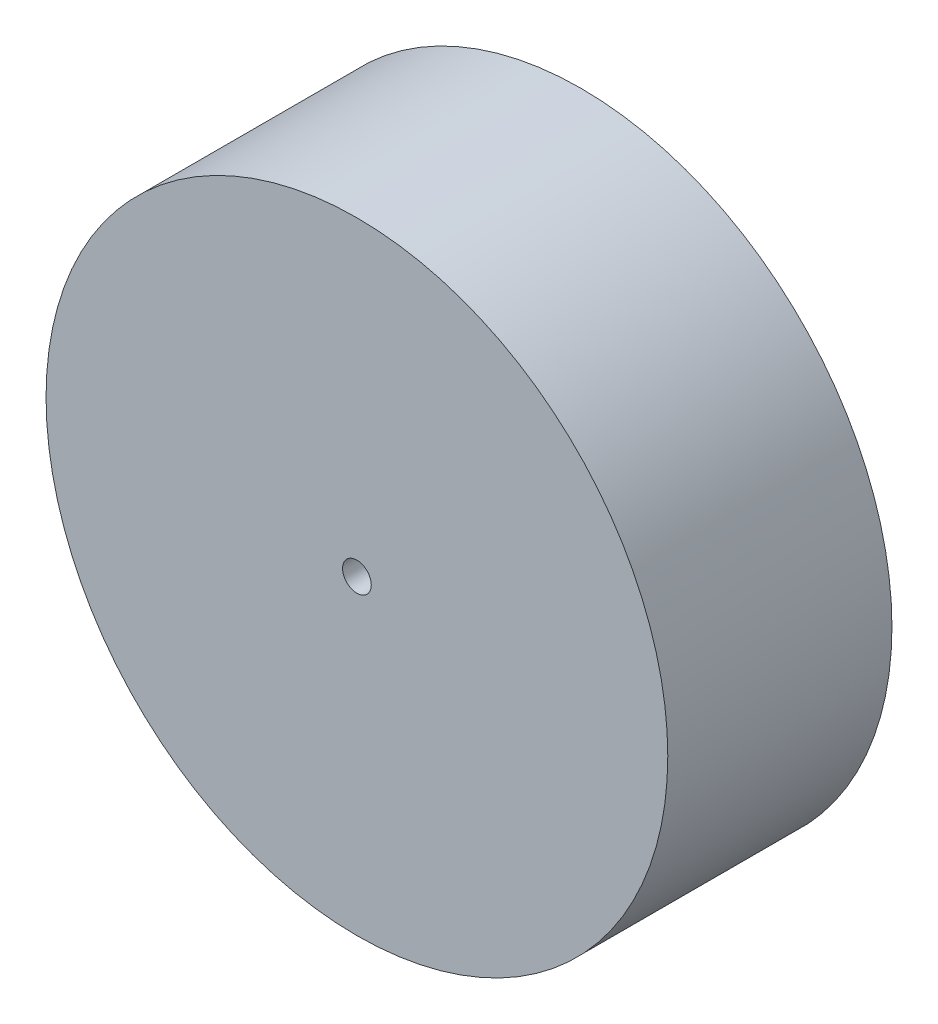
SolidWorks part; units mm, degrees
material "Rubber"
ref_plane "Front Plane" through (0, 0, 0) normal (0, 0, 1) x (1, 0, 0)
ref_plane "Top Plane" through (0, 0, 0) normal (0, 1, 0) x (1, 0, 0)
ref_plane "Right Plane" through (0, 0, 0) normal (1, 0, 0) x (0, 0, -1)
sketch "Sketch1" plane through (0, 0, 0) normal (0, 0, 1) x (1, 0, 0)
  circle A0 centre (0, 0) radius 34.671
  circle A1 centre (0, 0) radius 1.6
  dimension "D1" = 3.2
  dimension "D2" = 69.342
extrude "Boss-Extrude1" add sketch "Sketch1" along normal blind 25
